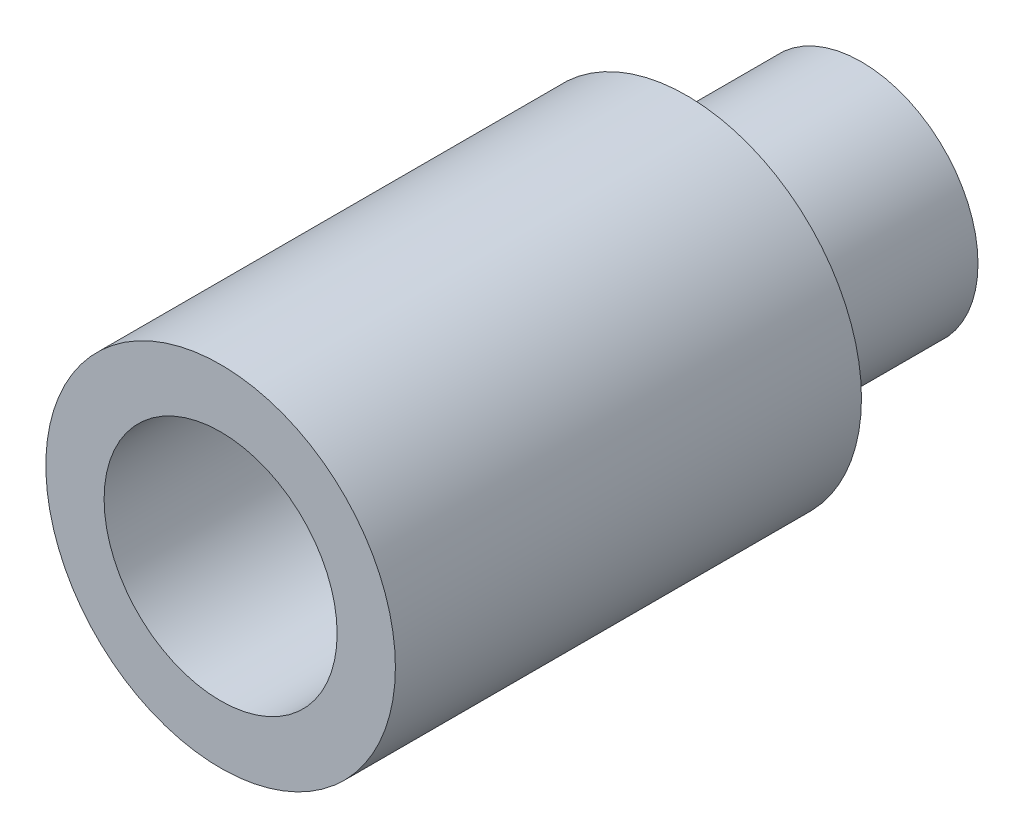
SolidWorks part; units mm, degrees
ref_plane "Front Plane" through (0, 0, 0) normal (0, 0, 1) x (1, 0, 0)
ref_plane "Top Plane" through (0, 0, 0) normal (0, 1, 0) x (1, 0, 0)
ref_plane "Right Plane" through (0, 0, 0) normal (1, 0, 0) x (0, 0, -1)
sketch "Sketch1" plane through (0, 0, 0) normal (0, 0, 1) x (1, 0, 0)
  circle A0 centre (0, 0) radius 6.35
  dimension "D1" = 12.7
extrude "Boss-Extrude1" add sketch "Sketch1" along normal blind 9.525
sketch "Sketch2" plane through (0, 0, 9.525) normal (0, 0, 1) x (1, 0, 0)
  circle A0 centre (0, 0) radius 9.525
  dimension "D1" = 19.05
extrude "Boss-Extrude2" add sketch "Sketch2" along normal blind 25.4
sketch "Sketch3" plane through (0, 0, 34.925) normal (0, 0, 1) x (1, 0, 0)
  circle A0 centre (0, 0) radius 6.35
  dimension "D1" = 12.7
extrude "Cut-Extrude1" cut sketch "Sketch3" against normal blind 19.05
